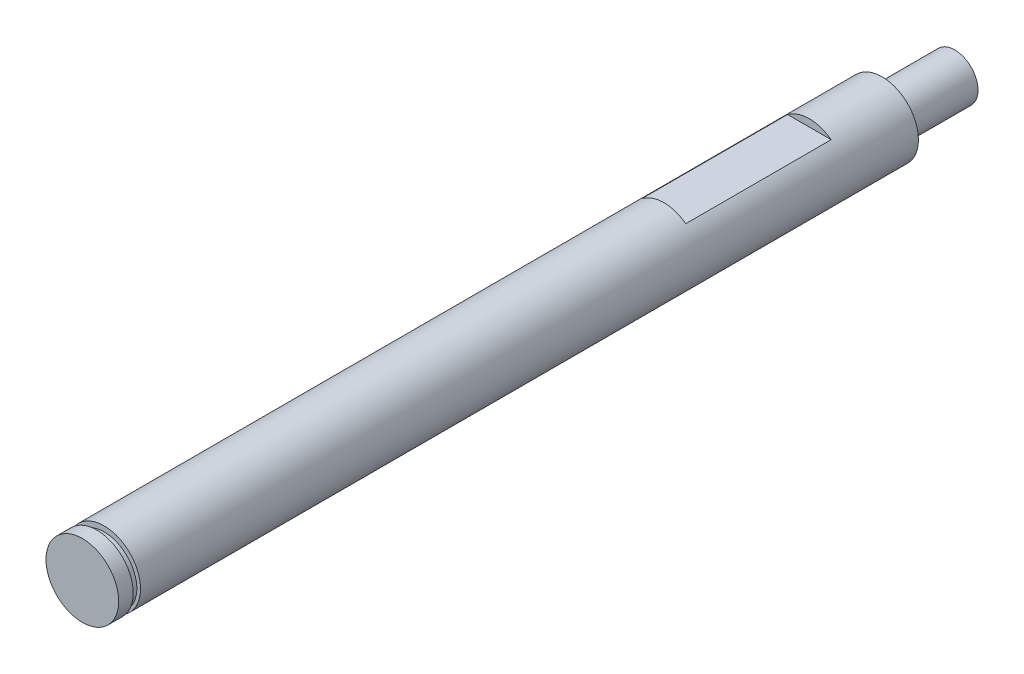
SolidWorks part; units mm, degrees
ref_plane "Front" through (0, 0, 0) normal (0, 0, 1) x (1, 0, 0)
ref_plane "Top" through (0, 0, 0) normal (0, 1, 0) x (1, 0, 0)
ref_plane "Right" through (0, 0, 0) normal (1, 0, 0) x (0, 0, -1)
sketch "Sketch1" plane through (0, 0, 0) normal (0, 0, 1) x (1, 0, 0)
  circle A0 centre (0, 0) radius 1.6
  dimension "D1" = 3.2
extrude "Boss-Extrude1" add sketch "Sketch1" along normal blind 5
cosmetic thread "Cosmetic Thread1" parameters "D2"=2.439
sketch "Sketch2" plane through (0, 0, 5) normal (0, 0, 1) x (1, 0, 0)
  circle A0 centre (0, 0) radius 2.5
  dimension "D1" = 5
extrude "Boss-Extrude2" add sketch "Sketch2" along normal blind 55
ref_plane "Plane1" through (0, 0, 54) normal (-1, 0, 0) x (0, 1, 0)
sketch "Sketch4" plane through (0, 0, 54) normal (-1, 0, 0) x (0, 1, 0)
  line L0 (4.1, -5) -> (2.14, -5)
  line L1 (2.14, -5) -> (2.14, -4.5)
  line L2 (2.14, -4.5) -> (4.1, -4.5)
  line L3 (4.2, -4.6) -> (4.2, -4.9)
  line L4 (-0.1056, -50) -> (-0.1056, 50) construction
  line L5 (-2.5, -6) -> (2.5, -6) construction
  line L6 (2.5, -6) -> (2.5, 49) construction
  arc A0 (4.2, -4.9) -> (4.1, -5) centre (4.1, -4.9) cw
  arc A1 (4.2, -4.6) -> (4.1, -4.5) centre (4.1, -4.6) ccw
  dimension "D1" = 0.1
  dimension "D2" = 0.1
  dimension "D3" = 0.5
  dimension "D4" = 1
  dimension "D5" = 0.36
revolve "Groove for ANSI B27.7 - 3BM1-8, Basic Internal Retaining Ring1" cut sketch "Sketch4"
ref_plane "Plane2" through (0, -2.5, 0) normal (0, -1, 0) x (1, 0, 0)
sketch "Sketch5" plane through (0, -2.5, 0) normal (0, -1, 0) x (1, 0, 0)
  line L0 (-2.5, 5) -> (2.5, 5) construction
  line L1 (3.7405, 10) -> (-4.5503, 10)
  line L2 (3.7405, 10) -> (3.7405, 20)
  line L3 (3.7405, 20) -> (-4.5503, 20)
  line L4 (-4.5503, 10) -> (-4.5503, 20)
  dimension "D1" = 5
  dimension "D2" = 10
extrude "Cut-Extrude1" cut sketch "Sketch5" against normal blind 0.5
mirror "Mirror1" about plane through (0, 0, 0) normal (0, 1, 0) of "Cut-Extrude1"
